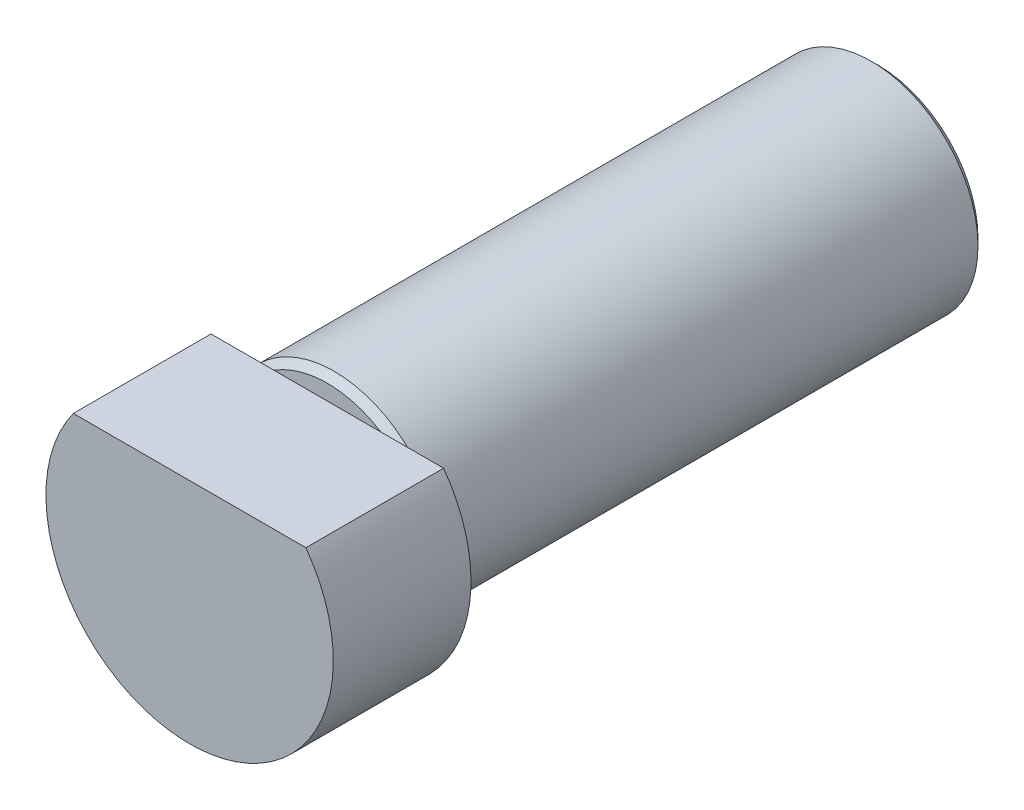
SolidWorks part; units mm, degrees
ref_plane "Front Plane" through (0, 0, 0) normal (0, 0, 1) x (1, 0, 0)
ref_plane "Top Plane" through (0, 0, 0) normal (0, 1, 0) x (1, 0, 0)
ref_plane "Right Plane" through (0, 0, 0) normal (1, 0, 0) x (0, 0, -1)
sketch "Sketch2" plane through (0, 0, 0) normal (0, 0, 1) x (1, 0, 0)
  circle A0 centre (0, 0) radius 0.775
  dimension "D1" = 1.55
extrude "Boss-Extrude1" add sketch "Sketch2" along normal blind 4
chamfer "Chamfer2" distance 0.05 angle 45 2 edges at (0.775, 0, 4) (0.775, 0, 0)
sketch "Sketch3" plane through (0, 0, 4) normal (0, 0, 1) x (1, 0, 0)
  line L0 (-0.8446, 0.6126) -> (0.8446, 0.6126) construction
  line L1 (-0.8446, 0.6126) -> (0.8446, 0.6126)
  arc A0 (-0.8446, 0.6126) -> (0.8446, 0.6126) centre (0, 0) ccw
extrude "Boss-Extrude2" add sketch "Sketch3" along normal blind 1
